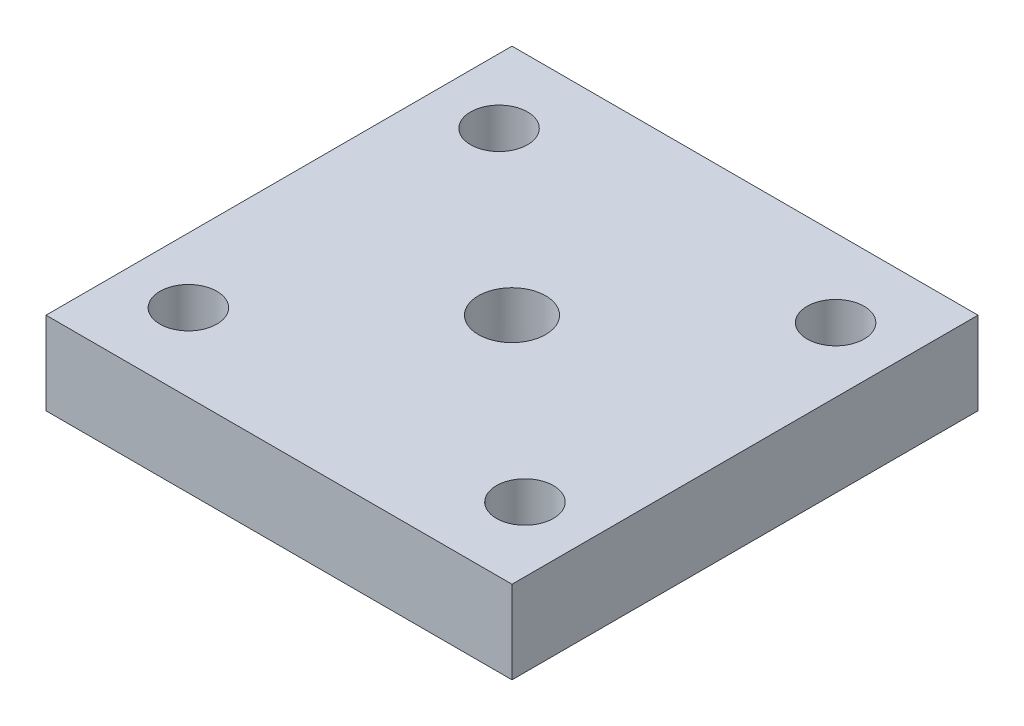
SolidWorks part; units mm, degrees
ref_plane "前视基准面" through (0, 0, 0) normal (0, 0, 1) x (1, 0, 0)
ref_plane "上视基准面" through (0, 0, 0) normal (0, 1, 0) x (1, 0, 0)
ref_plane "右视基准面" through (0, 0, 0) normal (1, 0, 0) x (0, 0, -1)
sketch "草图1" plane through (0, 0, 0) normal (0, 1, 0) x (1, 0, 0)
  line L1 (-22.5, 22.5) -> (22.5, 22.5)
  line L2 (-22.5, 22.5) -> (-22.5, -22.5)
  line L3 (-22.5, -22.5) -> (22.5, -22.5)
  line L4 (22.5, 22.5) -> (22.5, -22.5)
  dimension "D1" = 45
  dimension "D2" = 45
  dimension "D3" = 22.5
  dimension "D4" = 22.5
extrude "凸台-拉伸1" add sketch "草图1" along normal blind 8
sketch "草图2" plane through (0, 8, 0) normal (0, 1, 0) x (1, 0, 0)
  line L0 (-22.5, 22.5) -> (-22.5, -22.5) construction
  line L1 (-22.5, -22.5) -> (22.5, -22.5) construction
  circle A0 centre (-16.25, 15) radius 2.75
  circle A1 centre (16.25, 15) radius 2.75
  circle A2 centre (16.25, -15) radius 2.75
  circle A3 centre (-16.25, -15) radius 2.75
  dimension "D1" = 32.5
  dimension "D2" = 30
  dimension "D3" = 5.5
  dimension "D4" = 5.5
  dimension "D5" = 5.5
  dimension "D6" = 5.5
  dimension "D7" = 32.5
  dimension "D8" = 30
  dimension "D9" = 6.25
  dimension "D10" = 7.5
extrude "切除-拉伸1" cut sketch "草图2" against normal blind 8
sketch "草图3" plane through (0, 8, 0) normal (0, 1, 0) x (1, 0, 0)
  circle A0 centre (0, 0) radius 3.25
  dimension "D1" = 6.5
extrude "切除-拉伸2" cut sketch "草图3" against normal blind 8
sketch "草图4" plane through (0, 0, 0) normal (0, -1, 0) x (1, 0, 0)
  circle A0 centre (0, 0) radius 7
extrude "切除-拉伸3" cut sketch "草图4" against normal blind 3
